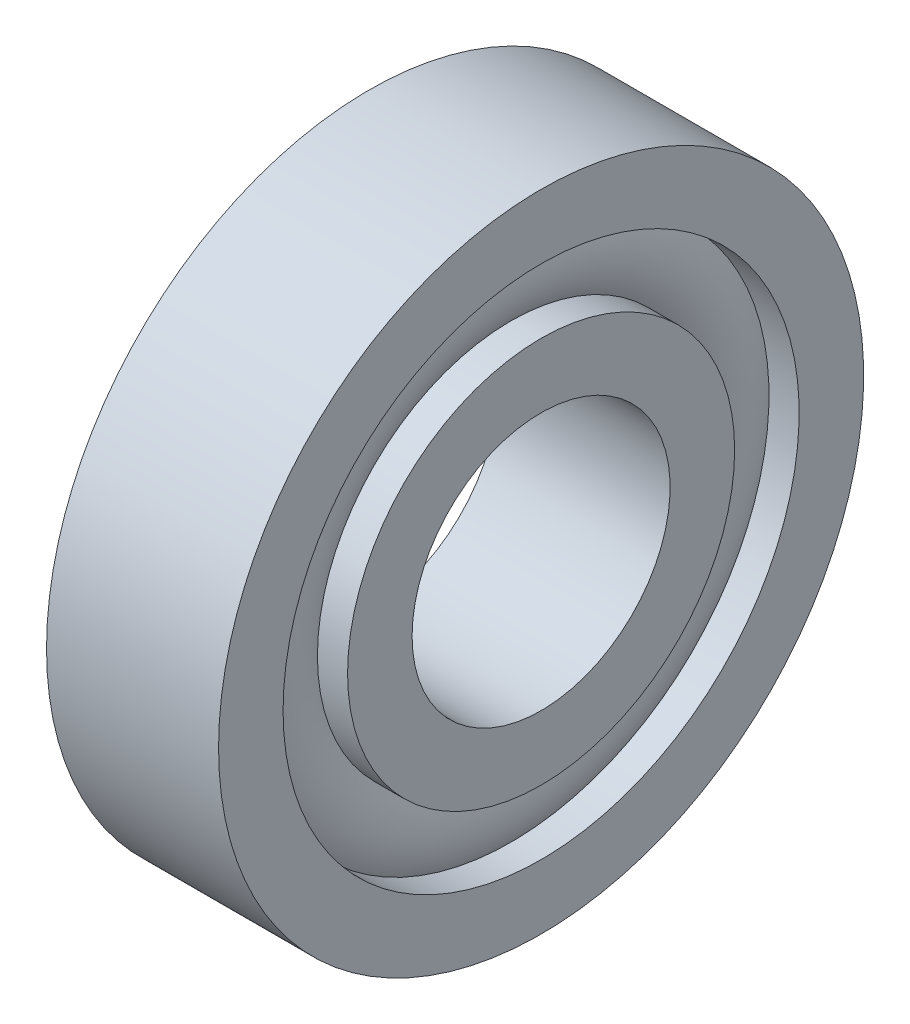
SolidWorks part; units mm, degrees
material "1.2083 (X40Cr14)"
ref_plane "Plan de face" through (0, 0, 0) normal (0, 0, 1) x (1, 0, 0)
ref_plane "Plan de dessus" through (0, 0, 0) normal (0, 1, 0) x (1, 0, 0)
ref_plane "Plan de droite" through (0, 0, 0) normal (1, 0, 0) x (0, 0, -1)
sketch "Esquisse1" plane through (0, 0, 0) normal (0, 0, 1) x (1, 0, 0)
  line L0 (-4, 6) -> (4, 6)
  line L1 (4, 6) -> (4, 9)
  line L2 (4, 9) -> (2.5981, 9)
  line L3 (0, 6) -> (0, 15) construction
  line L4 (-4, 0) -> (4, 0) construction
  line L5 (0, 10.5) -> (3, 10.5) construction
  line L6 (-4, 9) -> (-2.5981, 9)
  line L7 (-4, 6) -> (-4, 9)
  line L8 (-4, 15) -> (-4, 12)
  line L9 (-4, 12) -> (-2.5981, 12)
  line L10 (4, 12) -> (2.5981, 12)
  line L11 (4, 15) -> (4, 12)
  line L12 (-4, 15) -> (4, 15)
  arc A0 (2.5981, 9) -> (2.5981, 12) centre (0, 10.5) ccw
  arc A1 (-2.5981, 9) -> (-2.5981, 12) centre (0, 10.5) cw
  dimension "D5" = 3
  dimension "D1" = 12
  dimension "D2" = 30
  dimension "D3" = 8
  dimension "D4" = 3
revolve "Révolution1" add sketch "Esquisse1" angle 360 about L4
equation "\"D5@Esquisse1\"=\"D4@Esquisse1\""
